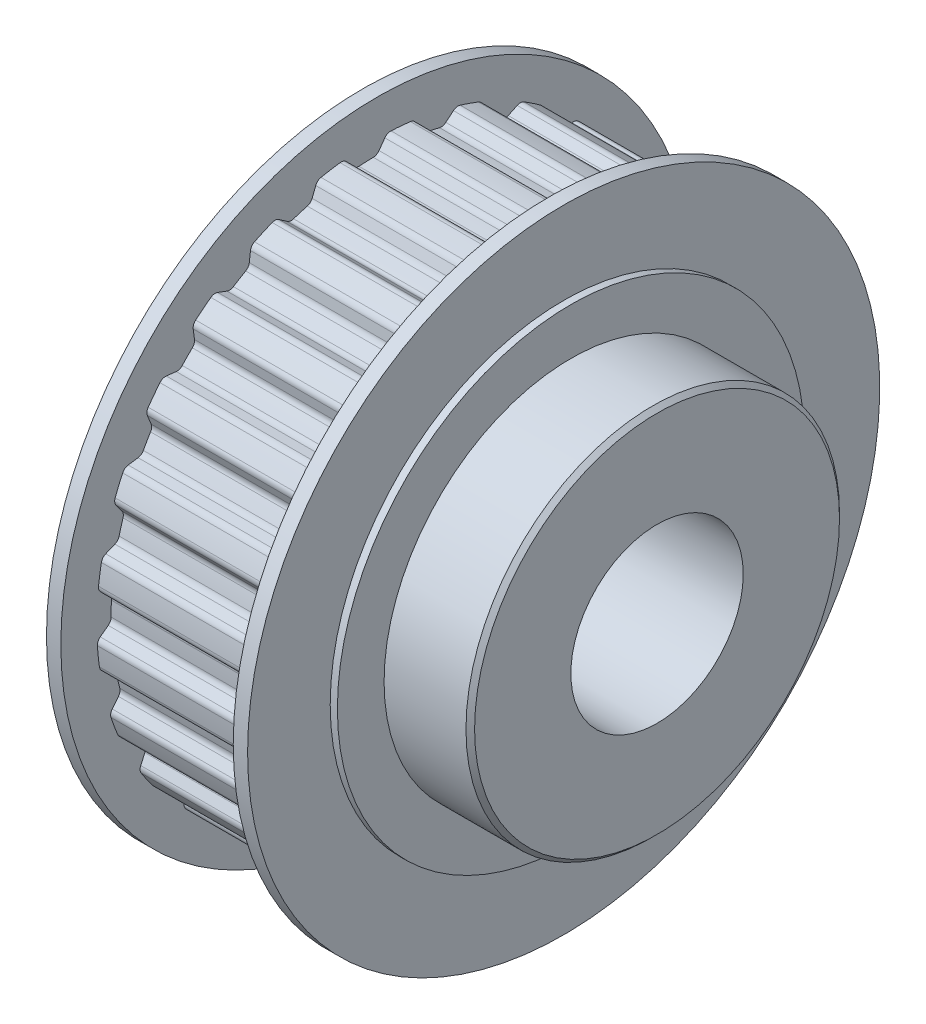
SolidWorks part; units mm, degrees
ref_plane "Front Plane" through (0, 0, 0) normal (0, 0, 1) x (1, 0, 0)
ref_plane "Top Plane" through (0, 0, 0) normal (0, 1, 0) x (1, 0, 0)
ref_plane "Right Plane" through (0, 0, 0) normal (1, 0, 0) x (0, 0, -1)
sketch "Sketch1" plane through (0, 0, 0) normal (0, 0, 1) x (1, 0, 0)
  line L0 (0, 0) -> (0, 16.25)
  line L1 (0, 16.25) -> (0.5, 16.25)
  line L2 (0.5, 16.25) -> (0.5, 22)
  line L3 (0.5, 22) -> (1.5, 22)
  line L4 (1.5, 22) -> (1.5, 19.5)
  line L5 (1.5, 19.5) -> (13.5, 19.5)
  line L6 (13.5, 19.5) -> (13.5, 22)
  line L7 (13.5, 22) -> (14.5, 22)
  line L8 (14.5, 22) -> (14.5, 16.25)
  line L9 (14.5, 16.25) -> (15, 16.25)
  line L10 (15, 16.25) -> (15, 13)
  line L11 (15, 13) -> (21, 13)
  line L12 (21, 13) -> (21, 0)
  line L13 (0, 0) -> (21, 0) construction
  line L14 (0, 0) -> (21, 0)
  dimension "D1" = 26
  dimension "D2" = 32.5
  dimension "D3" = 44
  dimension "D4" = 39
  dimension "D5" = 14
  dimension "D6" = 1
  dimension "D7" = 1
  dimension "D8" = 21
  dimension "D9" = 6
revolve "Revolve1" add sketch "Sketch1" angle 360 about L13
ref_plane "Plane1" through (1.5, 0, 0) normal (-1, 0, 0) x (0, 0, 1)
sketch "Sketch2" plane through (1.5, 0, 0) normal (-1, 0, 0) x (0, 0, 1)
  line L0 (2.2888, 19.3652) -> (1.5, 18.4391)
  line L1 (0, 18.5) -> (-0.7112, 19.487)
  line L2 (4.6008, 17.9188) -> (4.1574, 19.0517)
  line L3 (7.0329, 18.1876) -> (6.0385, 17.4868)
  line L4 (8.9124, 16.2117) -> (8.7648, 17.4192)
  line L5 (11.335, 15.8672) -> (10.1976, 15.4357)
  line L6 (12.6641, 13.4859) -> (12.8214, 14.6923)
  line L7 (14.9249, 12.5498) -> (13.7159, 12.4147)
  line L8 (15.6201, 9.9128) -> (16.0724, 11.0421)
  line L9 (17.577, 8.4439) -> (16.3724, 8.6137)
  line L10 (17.5945, 5.7168) -> (18.3135, 6.6982)
  line L11 (19.1247, 3.8074) -> (18.0001, 4.2714)
  line L12 (18.4635, 1.1616) -> (19.4039, 1.9334)
  line L13 (19.4707, -1.0684) -> (18.4969, -0.3392)
  line L14 (18.1723, -3.4666) -> (19.2751, -2.9529)
  line L15 (18.5933, -5.877) -> (17.8314, -4.9286)
  line L16 (16.7393, -7.8769) -> (17.9352, -7.6537)
  line L17 (16.5476, -10.3163) -> (16.0455, -9.2082)
  line L18 (14.2545, -11.7923) -> (15.4683, -11.8735)
  line L19 (13.4622, -14.1074) -> (13.2514, -12.9093)
  line L20 (10.874, -14.9668) -> (12.0295, -15.3473)
  line L21 (9.5309, -17.0121) -> (9.6247, -15.7992)
  line L22 (6.8103, -17.2009) -> (7.8349, -17.8568)
  line L23 (5.0007, -18.8479) -> (5.3932, -17.6964)
  line L24 (2.3187, -18.3541) -> (3.1479, -19.2442)
  line L25 (0.1563, -19.4994) -> (0.8229, -18.4817)
  line L26 (-2.3187, -18.3541) -> (-1.7368, -19.4225)
  line L27 (-4.6979, -18.9256) -> (-3.7992, -18.1057)
  line L28 (-6.8103, -17.2009) -> (-6.5124, -18.3804)
  line L29 (-9.2569, -17.1627) -> (-8.1825, -16.592)
  line L30 (-10.874, -14.9668) -> (-10.8789, -16.1833)
  line L31 (-13.2343, -14.3214) -> (-12.0518, -14.0359)
  line L32 (-14.2545, -11.7923) -> (-14.5617, -12.9695)
  line L33 (-16.3801, -10.5803) -> (-15.1637, -10.5977)
  line L34 (-16.7393, -7.8769) -> (-17.3296, -8.9406)
  line L35 (-18.4967, -6.1743) -> (-17.3229, -6.4937)
  line L36 (-18.1723, -3.4666) -> (-19.0086, -4.3501)
  line L37 (-19.4511, -1.3804) -> (-18.3936, -1.9817)
  line L38 (-18.4635, 1.1616) -> (-19.4932, 0.5138)
  line L39 (-19.1833, 3.5003) -> (-18.3085, 2.6548)
  line L40 (-17.5945, 5.7168) -> (-18.753, 5.3455)
  line L41 (-17.7101, 8.161) -> (-17.0731, 7.1246)
  line L42 (-15.6201, 9.9128) -> (-16.8345, 9.8412)
  line L43 (-15.1242, 12.3089) -> (-14.7649, 11.1466)
  line L44 (-12.6641, 13.4859) -> (-13.8582, 13.7186)
  line L45 (-11.5879, 15.6834) -> (-11.529, 14.4683)
  line L46 (-8.9124, 16.2117) -> (-10.0111, 16.734)
  line L47 (-7.3235, 18.0725) -> (-7.5686, 16.8809)
  line L48 (-4.6008, 17.9188) -> (-5.535, 18.6979)
  line L49 (-2.599, 19.326) -> (-3.1327, 18.2328)
  arc A0 (2.2888, 19.3652) -> (-0.7112, 19.487) centre (0, 0) ccw
  arc A1 (1.5, 18.4391) -> (0, 18.5) centre (0, 0) ccw
  arc A2 (7.0329, 18.1876) -> (4.1574, 19.0517) centre (0, 0) ccw
  arc A3 (6.0385, 17.4868) -> (4.6008, 17.9188) centre (0, 0) ccw
  arc A4 (11.335, 15.8672) -> (8.7648, 17.4192) centre (0, 0) ccw
  arc A5 (10.1976, 15.4357) -> (8.9124, 16.2117) centre (0, 0) ccw
  arc A6 (14.9249, 12.5498) -> (12.8214, 14.6923) centre (0, 0) ccw
  arc A7 (13.7159, 12.4147) -> (12.6641, 13.4859) centre (0, 0) ccw
  arc A8 (17.577, 8.4439) -> (16.0724, 11.0421) centre (0, 0) ccw
  arc A9 (16.3724, 8.6137) -> (15.6201, 9.9128) centre (0, 0) ccw
  arc A10 (19.1247, 3.8074) -> (18.3135, 6.6982) centre (0, 0) ccw
  arc A11 (18.0001, 4.2714) -> (17.5945, 5.7168) centre (0, 0) ccw
  arc A12 (19.4707, -1.0684) -> (19.4039, 1.9334) centre (0, 0) ccw
  arc A13 (18.4969, -0.3392) -> (18.4635, 1.1616) centre (0, 0) ccw
  arc A14 (18.5933, -5.877) -> (19.2751, -2.9529) centre (0, 0) ccw
  arc A15 (17.8314, -4.9286) -> (18.1723, -3.4666) centre (0, 0) ccw
  arc A16 (16.5476, -10.3163) -> (17.9352, -7.6537) centre (0, 0) ccw
  arc A17 (16.0455, -9.2082) -> (16.7393, -7.8769) centre (0, 0) ccw
  arc A18 (13.4622, -14.1074) -> (15.4683, -11.8735) centre (0, 0) ccw
  arc A19 (13.2514, -12.9093) -> (14.2545, -11.7923) centre (0, 0) ccw
  arc A20 (9.5309, -17.0121) -> (12.0295, -15.3473) centre (0, 0) ccw
  arc A21 (9.6247, -15.7992) -> (10.874, -14.9668) centre (0, 0) ccw
  arc A22 (5.0007, -18.8479) -> (7.8349, -17.8568) centre (0, 0) ccw
  arc A23 (5.3932, -17.6964) -> (6.8103, -17.2009) centre (0, 0) ccw
  arc A24 (0.1563, -19.4994) -> (3.1479, -19.2442) centre (0, 0) ccw
  arc A25 (0.8229, -18.4817) -> (2.3187, -18.3541) centre (0, 0) ccw
  arc A26 (-4.6979, -18.9256) -> (-1.7368, -19.4225) centre (0, 0) ccw
  arc A27 (-3.7992, -18.1057) -> (-2.3187, -18.3541) centre (0, 0) ccw
  arc A28 (-9.2569, -17.1627) -> (-6.5124, -18.3804) centre (0, 0) ccw
  arc A29 (-8.1825, -16.592) -> (-6.8103, -17.2009) centre (0, 0) ccw
  arc A30 (-13.2343, -14.3214) -> (-10.8789, -16.1833) centre (0, 0) ccw
  arc A31 (-12.0518, -14.0359) -> (-10.874, -14.9668) centre (0, 0) ccw
  arc A32 (-16.3801, -10.5803) -> (-14.5617, -12.9695) centre (0, 0) ccw
  arc A33 (-15.1637, -10.5977) -> (-14.2545, -11.7923) centre (0, 0) ccw
  arc A34 (-18.4967, -6.1743) -> (-17.3296, -8.9406) centre (0, 0) ccw
  arc A35 (-17.3229, -6.4937) -> (-16.7393, -7.8769) centre (0, 0) ccw
  arc A36 (-19.4511, -1.3804) -> (-19.0086, -4.3501) centre (0, 0) ccw
  arc A37 (-18.3936, -1.9817) -> (-18.1723, -3.4666) centre (0, 0) ccw
  arc A38 (-19.1833, 3.5003) -> (-19.4932, 0.5138) centre (0, 0) ccw
  arc A39 (-18.3085, 2.6548) -> (-18.4635, 1.1616) centre (0, 0) ccw
  arc A40 (-17.7101, 8.161) -> (-18.753, 5.3455) centre (0, 0) ccw
  arc A41 (-17.0731, 7.1246) -> (-17.5945, 5.7168) centre (0, 0) ccw
  arc A42 (-15.1242, 12.3089) -> (-16.8345, 9.8412) centre (0, 0) ccw
  arc A43 (-14.7649, 11.1466) -> (-15.6201, 9.9128) centre (0, 0) ccw
  arc A44 (-11.5879, 15.6834) -> (-13.8582, 13.7186) centre (0, 0) ccw
  arc A45 (-11.529, 14.4683) -> (-12.6641, 13.4859) centre (0, 0) ccw
  arc A46 (-7.3235, 18.0725) -> (-10.0111, 16.734) centre (0, 0) ccw
  arc A47 (-7.5686, 16.8809) -> (-8.9124, 16.2117) centre (0, 0) ccw
  arc A48 (-2.599, 19.326) -> (-5.535, 18.6979) centre (0, 0) ccw
  arc A49 (-3.1327, 18.2328) -> (-4.6008, 17.9188) centre (0, 0) ccw
  point P104 (0, 0)
  dimension "D1" = 39
  dimension "D3" = 37
  dimension "D2" = 1.5
  dimension "D4" = 3
  dimension "D5" = 25
extrude "Cut-Extrude1" cut sketch "Sketch2" against normal up to surface (12 mm away) up to face at (13.5, 0, 19.5)
fillet "Fillet1" radius 0.5 100 edges at (7.5, 17.9188, -4.6008) (7.5, 18.6979, -5.535) (7.5, 18.0725, -7.3235) (7.5, 16.8809, -7.5686) (7.5, 16.2117, -8.9124) (7.5, 16.734, -10.0111) (7.5, 15.6834, -11.5879) (7.5, 14.4683, -11.529) (7.5, 13.4859, -12.6641) (7.5, 13.7186, -13.8582) (7.5, 12.3089, -15.1242) (7.5, 11.1466, -14.7649) (7.5, 9.9128, -15.6201) (7.5, 9.8412, -16.8345) (7.5, 8.161, -17.7101) (7.5, 7.1246, -17.0731) (7.5, 5.7168, -17.5945) (7.5, 5.3455, -18.753) (7.5, 3.5003, -19.1833) (7.5, 2.6548, -18.3085) (7.5, 1.1616, -18.4635) (7.5, 0.5138, -19.4932) (7.5, -1.3804, -19.4511) (7.5, -1.9817, -18.3936) (7.5, -3.4666, -18.1723) (7.5, -4.3501, -19.0086) (7.5, -6.1743, -18.4967) (7.5, -6.4937, -17.3229) (7.5, -7.8769, -16.7393) (7.5, -8.9406, -17.3296) (7.5, -10.5803, -16.3801) (7.5, -10.5977, -15.1637) (7.5, -11.7923, -14.2545) (7.5, -12.9695, -14.5617) (7.5, -14.3214, -13.2343) (7.5, -14.0359, -12.0518) (7.5, -14.9668, -10.874) (7.5, -16.1833, -10.8789) (7.5, -17.1627, -9.2569) (7.5, -16.592, -8.1825) (7.5, -17.2009, -6.8103) (7.5, -18.3804, -6.5124) (7.5, -18.9256, -4.6979) (7.5, -18.1057, -3.7992) (7.5, -18.3541, -2.3187) (7.5, -19.4225, -1.7368) (7.5, -19.4994, 0.1563) (7.5, -18.4817, 0.8229) (7.5, -18.3541, 2.3187) (7.5, -19.2442, 3.1479) (7.5, -18.8479, 5.0007) (7.5, -17.6964, 5.3932) (7.5, -17.2009, 6.8103) (7.5, -17.8568, 7.8349) (7.5, -17.0121, 9.5309) (7.5, -15.7992, 9.6247) (7.5, -14.9668, 10.874) (7.5, -15.3473, 12.0295) (7.5, -14.1074, 13.4622) (7.5, -12.9093, 13.2514) (7.5, -11.7923, 14.2545) (7.5, -11.8735, 15.4683) (7.5, -10.3163, 16.5476) (7.5, -9.2082, 16.0455) (7.5, -7.8769, 16.7393) (7.5, -7.6537, 17.9352) (7.5, -5.877, 18.5933) (7.5, -4.9286, 17.8314) (7.5, -3.4666, 18.1723) (7.5, -2.9529, 19.2751) (7.5, -1.0684, 19.4707) (7.5, -0.3392, 18.4969) (7.5, 1.1616, 18.4635) (7.5, 1.9334, 19.4039) (7.5, 3.8074, 19.1247) (7.5, 4.2714, 18.0001) (7.5, 5.7168, 17.5945) (7.5, 6.6982, 18.3135) (7.5, 8.4439, 17.577) (7.5, 8.6137, 16.3724) (7.5, 9.9128, 15.6201) (7.5, 11.0421, 16.0724) (7.5, 12.5498, 14.9249) (7.5, 12.4147, 13.7159) (7.5, 13.4859, 12.6641) (7.5, 14.6923, 12.8214) (7.5, 16.2117, 8.9124) (7.5, 17.9188, 4.6008) (7.5, 15.4357, 10.1976) (7.5, 15.8672, 11.335) (7.5, 17.4192, 8.7648) (7.5, 18.1876, 7.0329) (7.5, 17.4868, 6.0385) (7.5, 19.0517, 4.1574) (7.5, 19.3652, 2.2888) (7.5, 18.4391, 1.5) (7.5, 18.5, 0) (7.5, 19.487, -0.7112) (7.5, 19.326, -2.599) (7.5, 18.2328, -3.1327)
sketch "Sketch3" plane through (21, 0, 0) normal (1, 0, 0) x (0, 0, -1)
  circle A0 centre (0, 0) radius 6
  dimension "D1" = 12
extrude "Cut-Extrude2" cut sketch "Sketch3" against normal through all
chamfer "Chamfer1" distance 0.3 angle 45 1 edges at (21, 0, 13)
